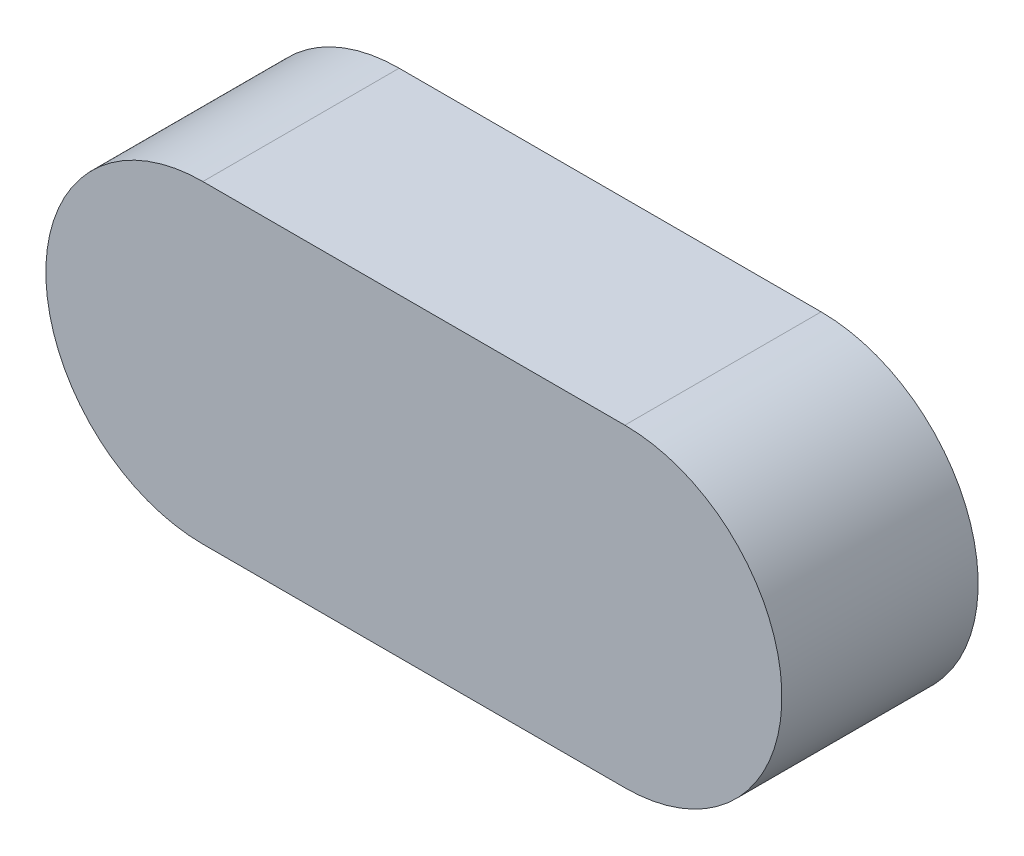
SolidWorks part; units mm, degrees
material "普通碳钢"
ref_plane "前视基准面" through (0, 0, 0) normal (0, 0, 1) x (1, 0, 0)
ref_plane "上视基准面" through (0, 0, 0) normal (0, 1, 0) x (1, 0, 0)
ref_plane "右视基准面" through (0, 0, 0) normal (1, 0, 0) x (0, 0, -1)
sketch "草图1" plane through (0, 0, 0) normal (0, 0, 1) x (1, 0, 0)
  line L0 (0, -27.4898) -> (0, 37.418) construction
  line L1 (-21.5, 16) -> (21.5, 16)
  line L3 (-21.5, -16) -> (21.5, -16)
  arc A0 (-21.5, 16) -> (-21.5, -16) centre (-21.5, 0) ccw
  arc A1 (21.5, 16) -> (21.5, -16) centre (21.5, 0) cw
  dimension "D1" = 43
  dimension "D3" = 32
  dimension "D4" = 16
extrude "拉伸1" add sketch "草图1" along normal blind 20
